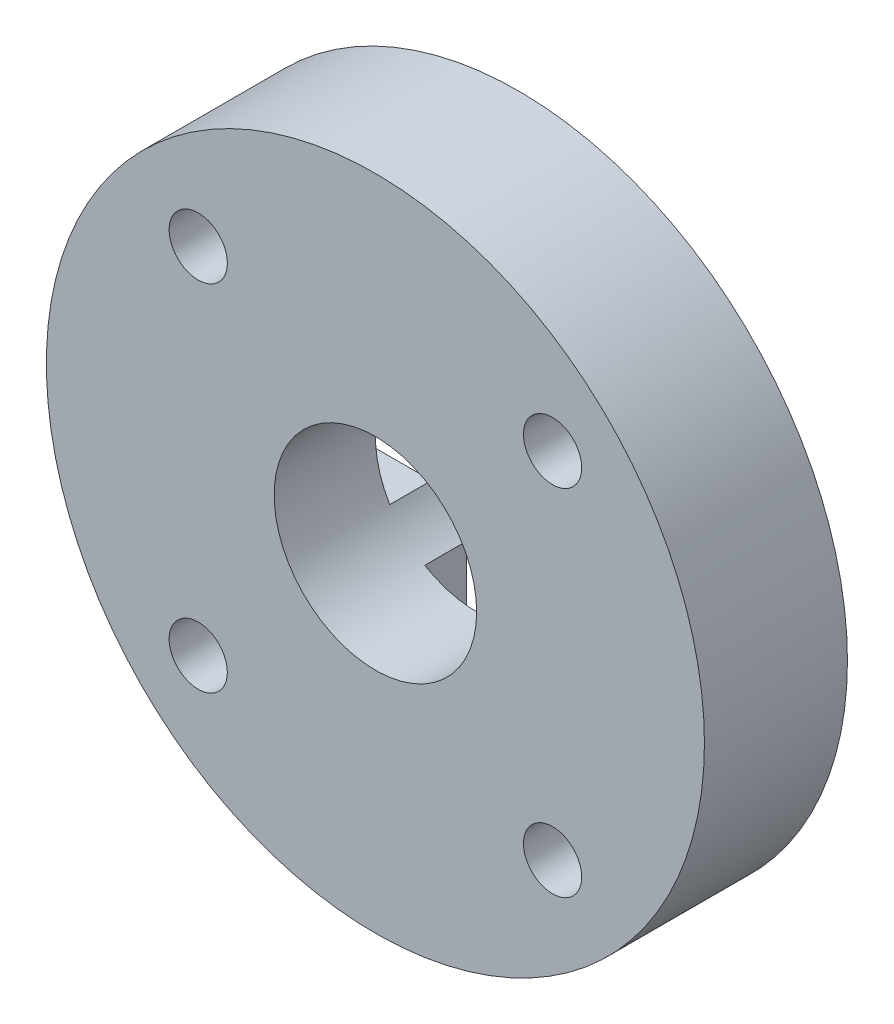
SolidWorks part; units mm, degrees
ref_plane "Front Plane" through (0, 0, 0) normal (0, 0, 1) x (1, 0, 0)
ref_plane "Top Plane" through (0, 0, 0) normal (0, 1, 0) x (1, 0, 0)
ref_plane "Right Plane" through (0, 0, 0) normal (1, 0, 0) x (0, 0, -1)
sketch "Trial_load_plate_profile" plane through (0, 0, 0) normal (0, 0, 1) x (1, 0, 0)
  circle A0 centre (0, 0) radius 13
  circle A1 centre (0, 0) radius 4
  dimension "D1" = 26
  dimension "D2" = 8
extrude "Trial_load_plate" add sketch "Trial_load_plate_profile" along normal blind 4
sketch "Captured_horn_key_boss_profile" plane through (0, 0, 0) normal (0, 0, 1) x (1, 0, 0)
  circle A0 centre (0, 0) radius 13
  dimension "D1" = 26
extrude "Captured_horn_key_boss" add sketch "Captured_horn_key_boss_profile" along normal blind 1.65 from offset 1.65
sketch "Stock_horn_pocket_Hub" plane through (0, 0, 0) normal (0, 0, 1) x (1, 0, 0)
  circle A0 centre (0, 0) radius 3.5
  dimension "D1" = 7
extrude "Key_pocket_Hub" cut sketch "Stock_horn_pocket_Hub" along normal blind 1.65 from offset 1.65
sketch "Stock_horn_pocket_Horizontal" plane through (0, 0, 0) normal (0, 0, 1) x (1, 0, 0)
  line L1 (-8.15, -2.05) -> (8.15, -2.05)
  line L2 (-8.15, -2.05) -> (-8.15, 2.05)
  line L3 (-8.15, 2.05) -> (8.15, 2.05)
  line L4 (8.15, -2.05) -> (8.15, 2.05)
  dimension "D1" = 16.3
  dimension "D2" = 4.1
extrude "Key_pocket_Horizontal" cut sketch "Stock_horn_pocket_Horizontal" along normal blind 1.65 from offset 1.65
sketch "Stock_horn_pocket_Vertical" plane through (0, 0, 0) normal (0, 0, 1) x (1, 0, 0)
  line L1 (-2.05, -8.15) -> (2.05, -8.15)
  line L2 (-2.05, -8.15) -> (-2.05, 8.15)
  line L3 (-2.05, 8.15) -> (2.05, 8.15)
  line L4 (2.05, -8.15) -> (2.05, 8.15)
  dimension "D1" = 4.1
  dimension "D2" = 16.3
extrude "Key_pocket_Vertical" cut sketch "Stock_horn_pocket_Vertical" along normal blind 1.65 from offset 1.65
sketch "Stock_horn_pocket_Rounded_tips" plane through (0, 0, 0) normal (0, 0, 1) x (1, 0, 0)
  circle A0 centre (8.15, 0) radius 2.05
  circle A1 centre (-8.15, 0) radius 2.05
  circle A2 centre (0, 8.15) radius 2.05
  circle A3 centre (0, -8.15) radius 2.05
  dimension "D1" = 4.1
  dimension "D2" = 4.1
  dimension "D3" = 4.1
  dimension "D4" = 4.1
extrude "Key_pocket_Rounded_tips" cut sketch "Stock_horn_pocket_Rounded_tips" along normal blind 1.65 from offset 1.65
sketch "Unmodified_horn_capture_M2_profile" plane through (0, 0, 0) normal (0, 0, 1) x (1, 0, 0)
  circle A0 centre (7, 7) radius 1.15
  circle A1 centre (-7, 7) radius 1.15
  circle A2 centre (-7, -7) radius 1.15
  circle A3 centre (7, -7) radius 1.15
  dimension "D1" = 2.3
  dimension "D2" = 2.3
  dimension "D3" = 2.3
  dimension "D4" = 2.3
extrude "Unmodified_horn_capture_M2" cut sketch "Unmodified_horn_capture_M2_profile" along normal through all from offset 50
sketch "Horn_center_hub_clearance" plane through (0, 0, 0) normal (0, 0, 1) x (1, 0, 0)
  circle A0 centre (0, 0) radius 4
  dimension "D1" = 8
extrude "Hub_clearance_in_key_boss_only" cut sketch "Horn_center_hub_clearance" along normal blind 1.65 from offset 1.65
